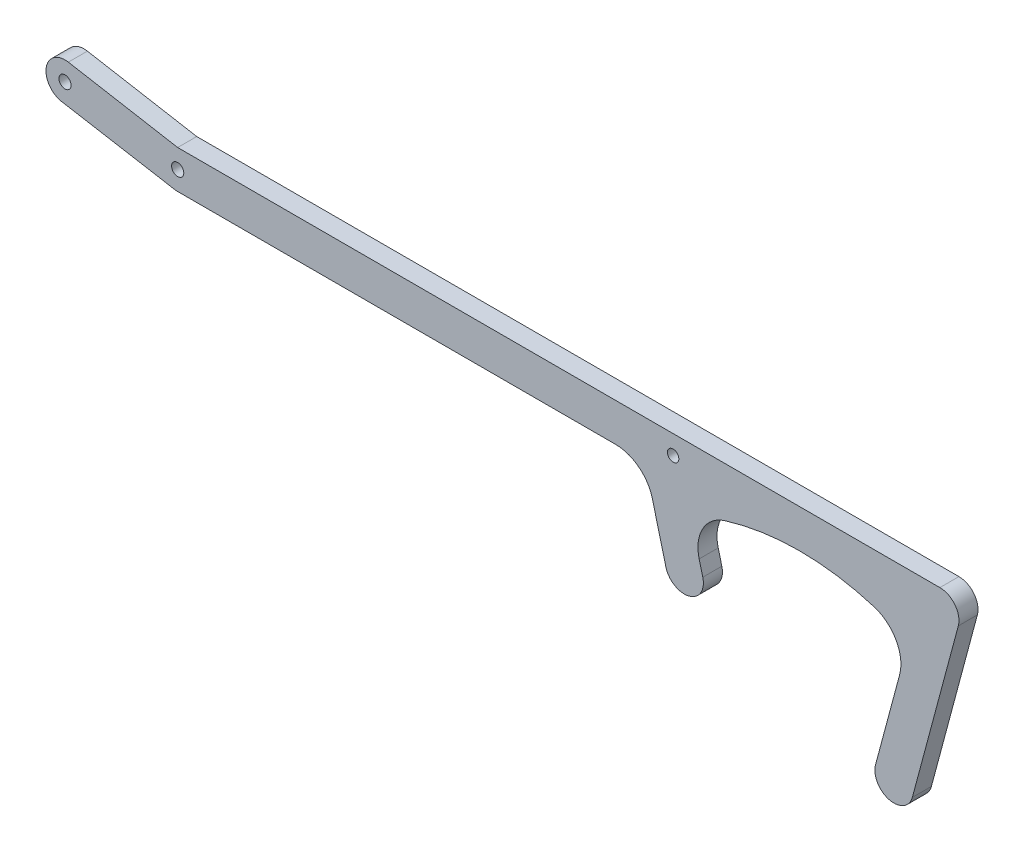
SolidWorks part; units mm, degrees
ref_plane "Front Plane" through (0, 0, 0) normal (0, 0, 1) x (1, 0, 0)
ref_plane "Top Plane" through (0, 0, 0) normal (0, 1, 0) x (1, 0, 0)
ref_plane "Right Plane" through (0, 0, 0) normal (1, 0, 0) x (0, 0, -1)
sketch "Sketch1" plane through (0, 0, 0) normal (0, 0, 1) x (1, 0, 0)
  line L0 (0, 0) -> (254, 0) construction
  line L1 (0, 6.35) -> (254, 6.35)
  line L2 (0, -6.35) -> (155.7202, -6.35)
  line L3 (260.1336, -1.6435) -> (244.8203, -58.7935)
  line L4 (232.5531, -55.5065) -> (243.5126, -14.605)
  line L6 (162.6883, -33.3375) -> (155.7202, -6.35)
  line L7 (174.9851, -30.1625) -> (170.9681, -14.605)
  line L8 (0, 0) -> (-37.5378, 6.521) construction
  line L10 (0, 6.35) -> (-36.4351, 12.7745)
  line L11 (-38.6246, 0.2647) -> (-1.0868, -6.2563)
  circle A0 centre (0, 0) radius 2.032
  arc A2 (260.1336, -1.6435) -> (254, 6.35) centre (254, 0) ccw
  arc A3 (232.5531, -55.5065) -> (244.8203, -58.7935) centre (238.6867, -57.15) ccw
  arc A5 (162.6883, -33.3375) -> (174.9851, -30.1625) centre (168.8367, -31.75) ccw
  arc A6 (170.9681, -14.605) -> (243.5126, -14.605) centre (207.2404, -90.8741) cw
  circle A7 centre (165.1, 0) radius 1.905
  arc A9 (-36.4351, 12.7745) -> (-38.6246, 0.2647) centre (-37.5378, 6.521) ccw
  circle A10 centre (-37.5378, 6.521) radius 2.032
  arc A12 (0, -6.35) -> (-1.0868, -6.2563) centre (0, 0) cw
  dimension "D1" = 31.75
  dimension "D3" = 6.35
  dimension "D5" = 6.35
  dimension "D6" = 6.35
  dimension "D11" = 4.064
  dimension "D14" = 17.145
  dimension "D10" = 75
  dimension "D13" = 84.455
  dimension "D15" = 3.81
  dimension "D19" = 6.35
  dimension "D21" = 4.064
  dimension "D17" = 6.35
  dimension "D4" = 12.7
  dimension "D7" = 254
  dimension "D8" = 57.15
  dimension "D9" = 69.85
  dimension "D12" = 26.9875
  dimension "D16" = 165.1
  dimension "D18" = 38.1
  dimension "D20" = 170
extrude "Boss-Extrude1" add sketch "Sketch1" along normal mid plane 6.35
fillet "Fillet1" radius 12.7 1 edges at (155.7202, -6.35, 0)
fillet "Fillet2" radius 12.7 2 edges at (243.5126, -14.605, 0) (170.9681, -14.605, 0)
